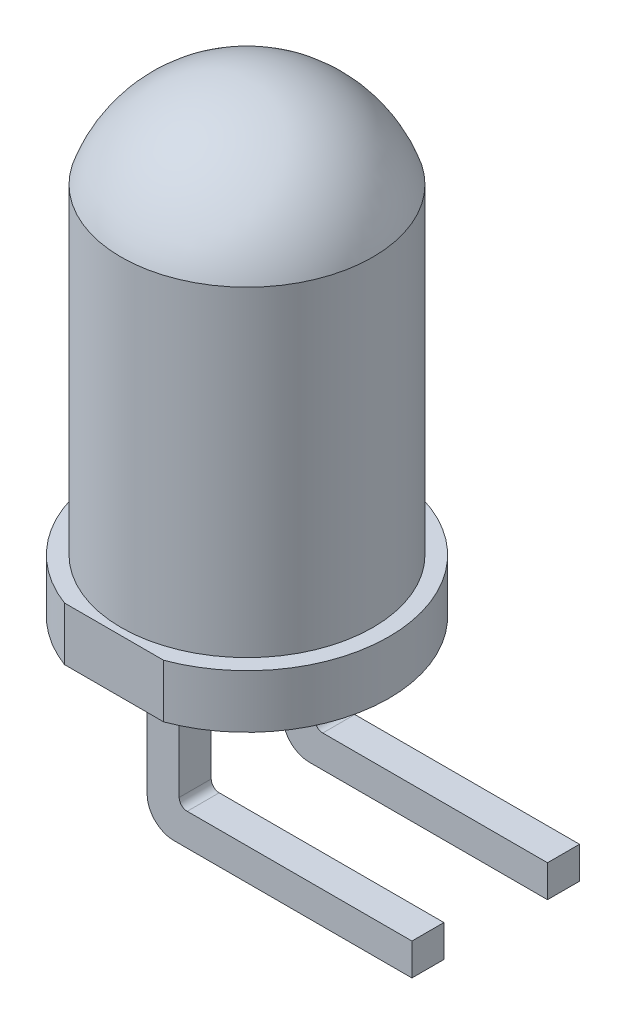
SolidWorks part; units mm, degrees
ref_plane "Ön Düzlem" through (0, 0, 0) normal (0, 0, 1) x (1, 0, 0)
ref_plane "Üst Düzlem" through (0, 0, 0) normal (0, 1, 0) x (1, 0, 0)
ref_plane "Sağ Düzlem" through (0, 0, 0) normal (1, 0, 0) x (0, 0, -1)
sketch "Çizim1" plane through (0, 0, 0) normal (0, 0, 1) x (1, 0, 0)
  line L0 (0, 8.7) -> (0, 0) construction
  line L1 (2.358, 7.01) -> (2.358, 1)
  line L2 (2.358, 1) -> (0, 1)
  line L3 (2.658, 0) -> (0, 0)
  line L4 (2.358, 1) -> (2.658, 1)
  line L5 (2.658, 1) -> (2.658, 0)
  line L6 (0, 0) -> (0, 8.7)
  arc A0 (0, 8.7) -> (2.358, 7.01) centre (0, 6.21) cw
  dimension "D1" = 2.49
  dimension "D2" = 8.7
  dimension "D3" = 0.3
  dimension "D4" = 1
  dimension "D5" = 6.01
revolve "Döndür1" add sketch "Çizim1" angle 360 about L0
sketch "Çizim2" plane through (0, 0, 0) normal (0, -1, 0) x (-1, 0, 0)
  line L1 (0.9299, -2.49) -> (-1.0701, -2.49)
  line L2 (0.9299, -2.49) -> (0.9299, -2.79)
  line L3 (0.9299, -2.79) -> (-1.0701, -2.79)
  line L4 (-1.0701, -2.49) -> (-1.0701, -2.79)
  circle A0 centre (0, 0) radius 2.658 construction
  dimension "D1" = 2.49
  dimension "D2" = 0.3
  dimension "D3" = 2
extrude "Kes-Ekstrüzyon3" cut sketch "Çizim2" against normal blind 10
sketch "Çizim3" plane through (0, 0, 0) normal (0, -1, 0) x (1, 0, 0)
  line L1 (0.3, 1.57) -> (-0.3, 1.57)
  line L2 (0.3, 1.57) -> (0.3, 0.97)
  line L3 (0.3, 0.97) -> (-0.3, 0.97)
  line L4 (-0.3, 1.57) -> (-0.3, 0.97)
  line L5 (0.3, 1.57) -> (-0.3, 0.97) construction
  line L6 (0.3, 0.97) -> (-0.3, 1.57) construction
  line L7 (0.3, -1.57) -> (-0.3, -1.57)
  line L8 (0.3, -1.57) -> (0.3, -0.97)
  line L9 (0.3, -0.97) -> (-0.3, -0.97)
  line L10 (-0.3, -1.57) -> (-0.3, -0.97)
  line L11 (0.3, -1.57) -> (-0.3, -0.97) construction
  line L12 (0.3, -0.97) -> (-0.3, -1.57) construction
  point P0 (0, 1.27)
  point P5 (0, -1.27)
  dimension "D1" = 1.27
  dimension "D2" = 2.54
  dimension "D3" = 0.6
  dimension "D4" = 0.6
  dimension "D5" = 0.6
  dimension "D6" = 0.6
  dimension "D7" = 2.84
  dimension "D8" = 1.27
extrude "Yükseklik-Ekstrüzyon1" add sketch "Çizim3" along normal blind 2.75
sketch "Çizim4" plane through (0.3, 0, 0) normal (1, 0, 0) x (0, 0, -1)
  line L0 (-0.97, -2.75) -> (-0.97, 0) construction
  line L1 (-1.57, -2.75) -> (-0.97, -2.75)
  line L2 (-1.57, -2.75) -> (-1.57, -2.15)
  line L3 (-1.57, -2.15) -> (-0.97, -2.15)
  line L4 (-0.97, -2.75) -> (-0.97, -2.15)
  line L5 (1.57, -2.75) -> (1.57, 0) construction
  line L6 (0.97, -2.75) -> (1.57, -2.75)
  line L7 (0.97, -2.75) -> (0.97, -2.15)
  line L8 (0.97, -2.15) -> (1.57, -2.15)
  line L9 (1.57, -2.75) -> (1.57, -2.15)
  dimension "D1" = 0.6
extrude "Yükseklik-Ekstrüzyon2" add sketch "Çizim4" along normal blind 4.36
fillet "Radyus1" radius 0.5 2 edges at (-0.3, -2.75, 1.27) (-0.3, -2.75, -1.27)
fillet "Radyus2" radius 0.15 1 edges at (0.3, -2.15, -1.27)
fillet "Radyus3" radius 0.15 1 edges at (0.3, -2.15, 1.27)
